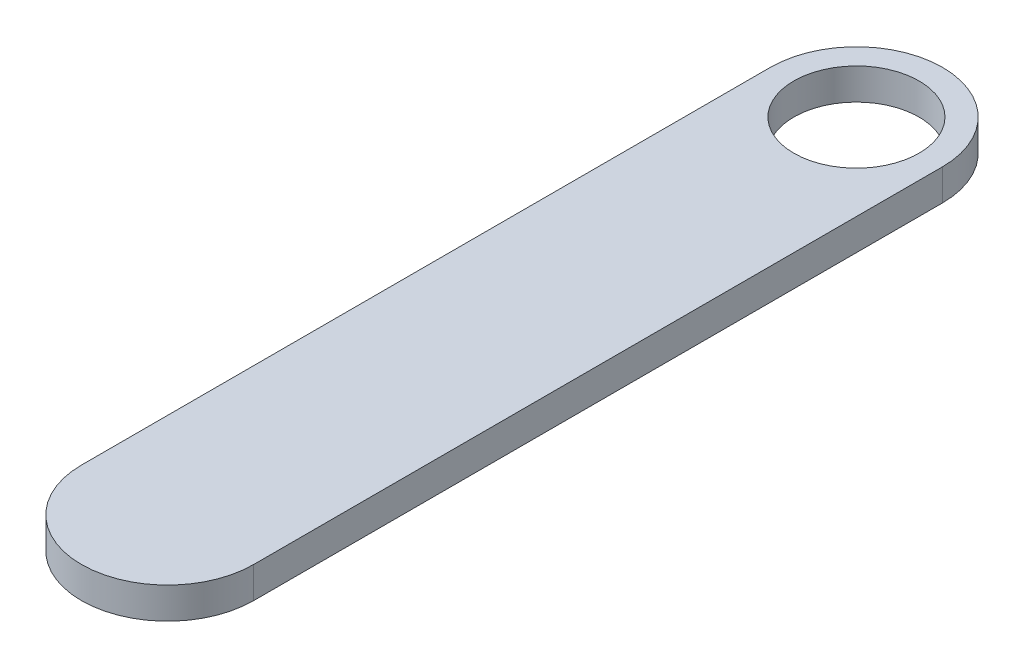
SolidWorks part; units mm, degrees
ref_plane "Front Plane" through (0, 0, 0) normal (0, 0, 1) x (1, 0, 0)
ref_plane "Top Plane" through (0, 0, 0) normal (0, 1, 0) x (1, 0, 0)
ref_plane "Right Plane" through (0, 0, 0) normal (1, 0, 0) x (0, 0, -1)
sketch "Sketch2" plane through (0, 0, 0) normal (0, 1, 0) x (1, 0, 0)
  line L0 (0, 0) -> (0, 44) construction
  line L1 (-5.5, 0) -> (-5.5, 44)
  line L2 (5.5, 0) -> (5.5, 44)
  arc A0 (-5.5, 0) -> (5.5, 0) centre (0, 0) ccw
  arc A1 (5.5, 44) -> (-5.5, 44) centre (0, 44) ccw
  circle A2 centre (0, 44) radius 4
  point P3 (0, 22)
  dimension "D3" = 8
  dimension "D1" = 11
  dimension "D2" = 44
extrude "Boss-Extrude1" add sketch "Sketch2" along normal blind 2
